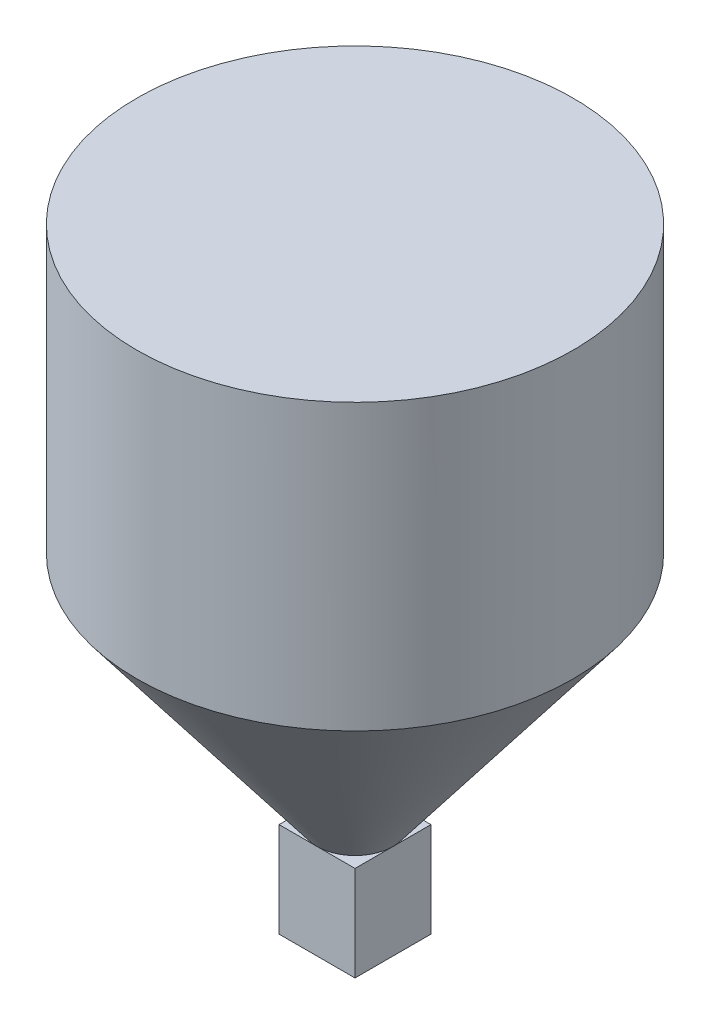
SolidWorks part; units mm, degrees
ref_plane "Alzado" through (0, 0, 0) normal (0, 0, 1) x (1, 0, 0)
ref_plane "Planta" through (0, 0, 0) normal (0, 1, 0) x (1, 0, 0)
ref_plane "Vista lateral" through (0, 0, 0) normal (1, 0, 0) x (0, 0, -1)
sketch "Croquis1" plane through (0, 0, 0) normal (0, 1, 0) x (1, 0, 0)
  circle A0 centre (0, 0) radius 115
  dimension "D1" = 230
ref_plane "Plano1" through (0, -274, 0) normal (0, 1, 0) x (1, 0, 0)
extrude "Saliente-Extruir1" add sketch "Croquis1" against normal blind 150 contours A0
sketch "Croquis2" plane through (0, -150, 0) normal (0, -1, 0) x (1, 0, 0)
  circle A1 centre (0, 0) radius 115
sketch "Croquis3" plane through (0, -274, 0) normal (0, 1, 0) x (1, 0, 0)
  circle A0 centre (0, 0) radius 20
  dimension "D1" = 40
loft "Recubrir1" add profiles "Croquis3", "Croquis2"
sketch "Croquis4" plane through (0, -274, 0) normal (0, -1, 0) x (1, 0, 0)
  line L1 (-20, -20) -> (20, -20)
  line L2 (-20, -20) -> (-20, 20)
  line L3 (-20, 20) -> (20, 20)
  line L4 (20, -20) -> (20, 20)
  line L5 (-20, -20) -> (20, 20) construction
  line L6 (-20, 20) -> (20, -20) construction
  point P0 (0, 0)
  dimension "D1" = 40
  dimension "D2" = 40
extrude "Saliente-Extruir2" add sketch "Croquis4" along normal blind 50
